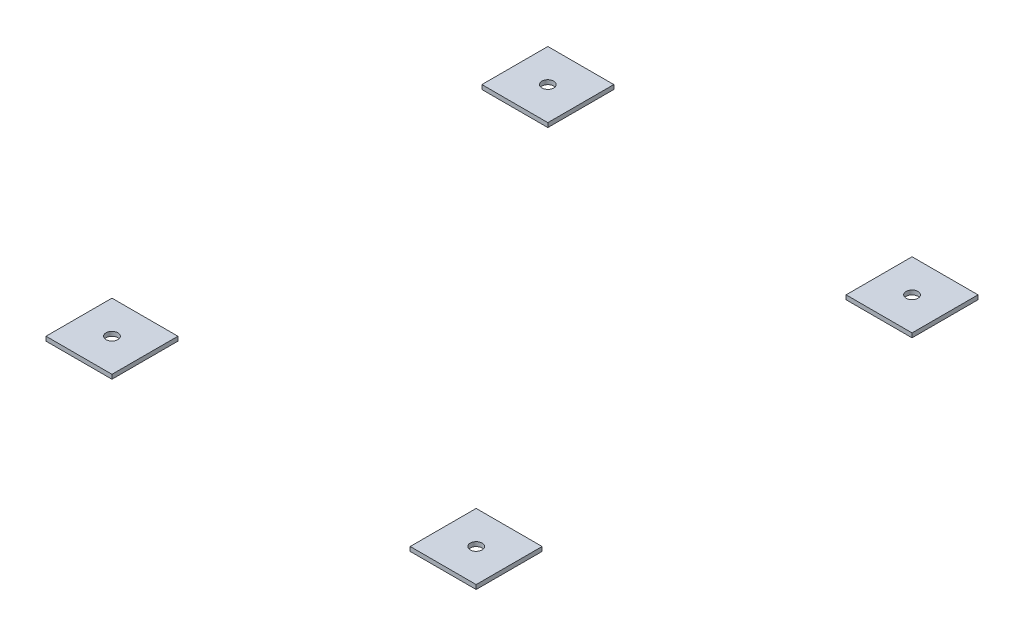
SolidWorks part; units mm, degrees
ref_plane "Front Plane" through (0, 0, 0) normal (0, 0, 1) x (1, 0, 0)
ref_plane "Top Plane" through (0, 0, 0) normal (0, 1, 0) x (1, 0, 0)
ref_plane "Right Plane" through (0, 0, 0) normal (1, 0, 0) x (0, 0, -1)
sketch "Sketch1" plane through (0, 0, 0) normal (0, 1, 0) x (1, 0, 0)
  line L1 (104, 129) -> (150, 129)
  line L2 (104, 129) -> (104, 175)
  line L3 (104, 175) -> (150, 175)
  line L4 (150, 129) -> (150, 175)
  line L5 (-150, 129) -> (-104, 129)
  line L6 (-150, 129) -> (-150, 175)
  line L7 (-150, 175) -> (-104, 175)
  line L8 (-104, 129) -> (-104, 175)
  line L9 (104, -175) -> (150, -175)
  line L10 (104, -175) -> (104, -129)
  line L11 (104, -129) -> (150, -129)
  line L12 (150, -175) -> (150, -129)
  line L13 (-150, -175) -> (-104, -175)
  line L14 (-150, -175) -> (-150, -129)
  line L15 (-150, -129) -> (-104, -129)
  line L16 (-104, -175) -> (-104, -129)
  circle A0 centre (127, 152) radius 4.14
  circle A1 centre (-127, 152) radius 4.14
  circle A2 centre (127, -152) radius 4.14
  circle A3 centre (-127, -152) radius 4.14
extrude "Electronics tray corner tabs" add sketch "Sketch1" along normal mid plane 3
